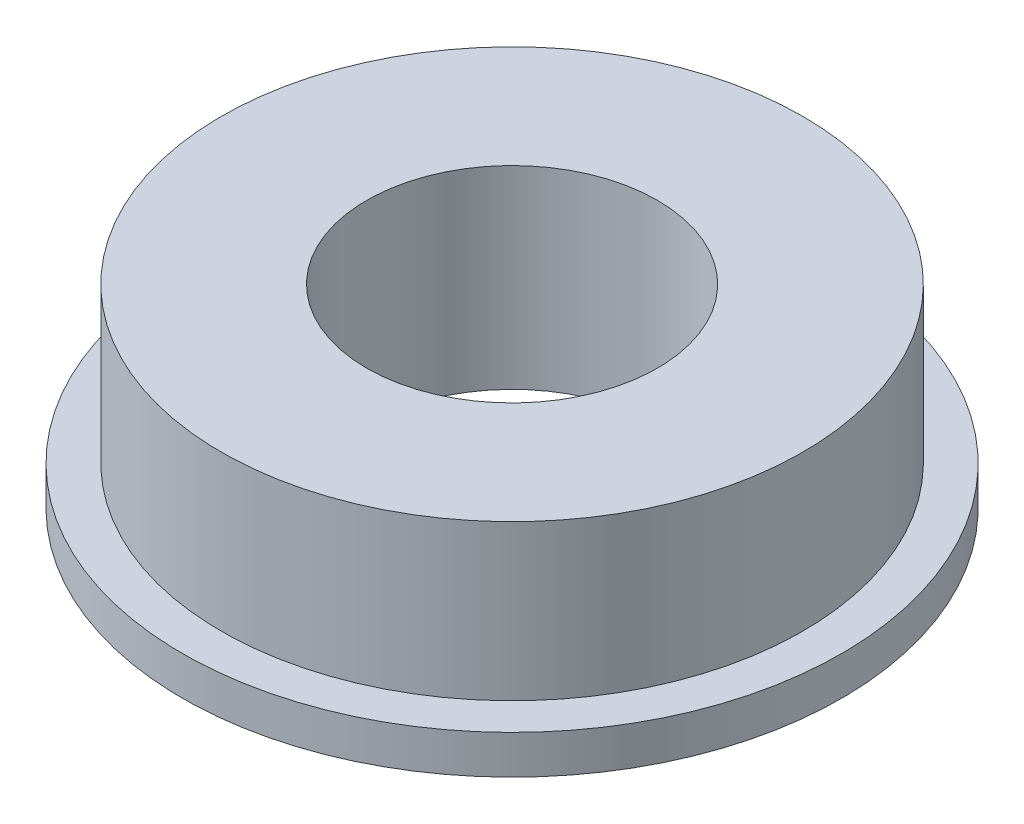
SolidWorks part; units mm, degrees
other "标注1"
sketch "草图2" plane through (6.8, 0, -6.8) normal (0.9032, -0.4176, -0.0991) x (-0.4173, -0.8005, -0.4301)
material "合金钢"
ref_plane "前视基准面" through (0, 0, 0) normal (0, 0, 1) x (1, 0, 0)
ref_plane "上视基准面" through (0, 0, 0) normal (0, 1, 0) x (1, 0, 0)
ref_plane "右视基准面" through (0, 0, 0) normal (1, 0, 0) x (0, 0, -1)
sketch "草图1" plane through (0, 0, 0) normal (0, 0, 1) x (1, 0, 0)
  line L0 (0, 0) -> (-3, 0)
  line L1 (-3, 0) -> (-6.8, 0)
  line L2 (-6.8, 0) -> (-6.8, 0.8)
  line L3 (-6.8, 0.8) -> (-6, 0.8)
  line L4 (-6, 0.8) -> (-6, 4)
  line L5 (-6, 4) -> (-3, 4)
  line L6 (-3, 4) -> (-3, 0)
  line L7 (0, 0) -> (0, 4.2316) construction
  dimension "D1" = 6
  dimension "D2" = 12
  dimension "D3" = 13.6
  dimension "D4" = 3.2
  dimension "D5" = 0.8
revolve "旋转1" add sketch "草图1" angle 360 about L7
